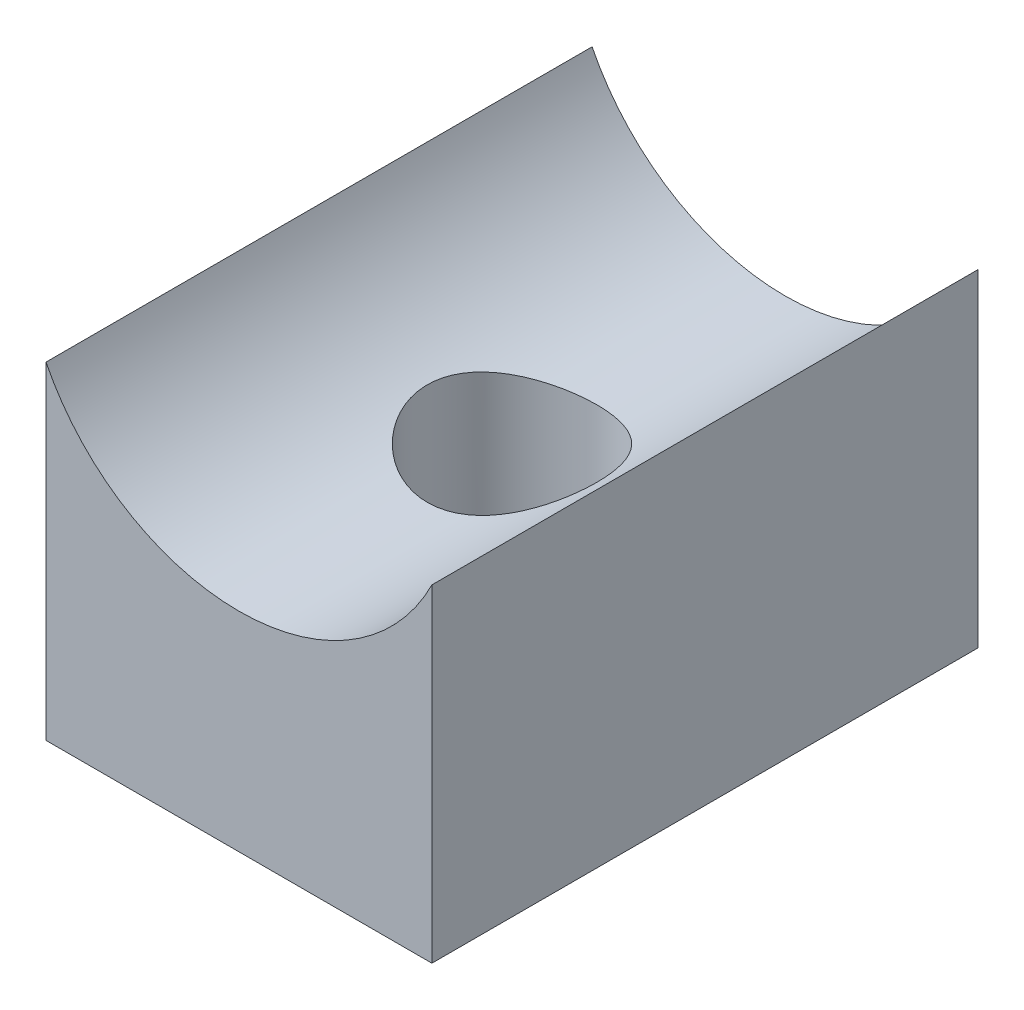
SolidWorks part; units mm, degrees
ref_plane "Front Plane" through (0, 0, 0) normal (0, 0, 1) x (1, 0, 0)
ref_plane "Top Plane" through (0, 0, 0) normal (0, 1, 0) x (1, 0, 0)
ref_plane "Right Plane" through (0, 0, 0) normal (1, 0, 0) x (0, 0, -1)
sketch "Sketch1" plane through (0, 0, 0) normal (0, 0, 1) x (1, 0, 0)
  line L0 (-3.5333, -6) -> (3.5333, -6)
  line L1 (3.5333, 0) -> (3.5333, -6)
  line L2 (-3.5333, 0) -> (-3.5333, -6)
  line L3 (55, 0) -> (-55, 0) construction
  line L4 (0, -44.7868) -> (0, 44.7868) construction
  arc A0 (-3.5333, 0) -> (3.5333, 0) centre (0, 1.7659) ccw
  point P2 (0, 0)
  point P3 (0, 0)
  point P10 (0, 0)
  point P11 (-14.5466, 0)
  point P12 (-15.9997, 0)
  point P13 (14.7596, 0)
  point P14 (0, 0)
  point P15 (0, 1.7659)
  dimension "D1" = 3.95
  dimension "D2" = 6
extrude "Boss-Extrude1" add sketch "Sketch1" along normal mid plane 10
sketch "Sketch2" plane through (0, -6, 0) normal (0, -1, 0) x (-1, 0, 0)
  circle A0 centre (0, 0) radius 1.55
  dimension "D1" = 3.1
extrude "Cut-Extrude1" cut sketch "Sketch2" against normal up to surface (3.8159 mm away)
